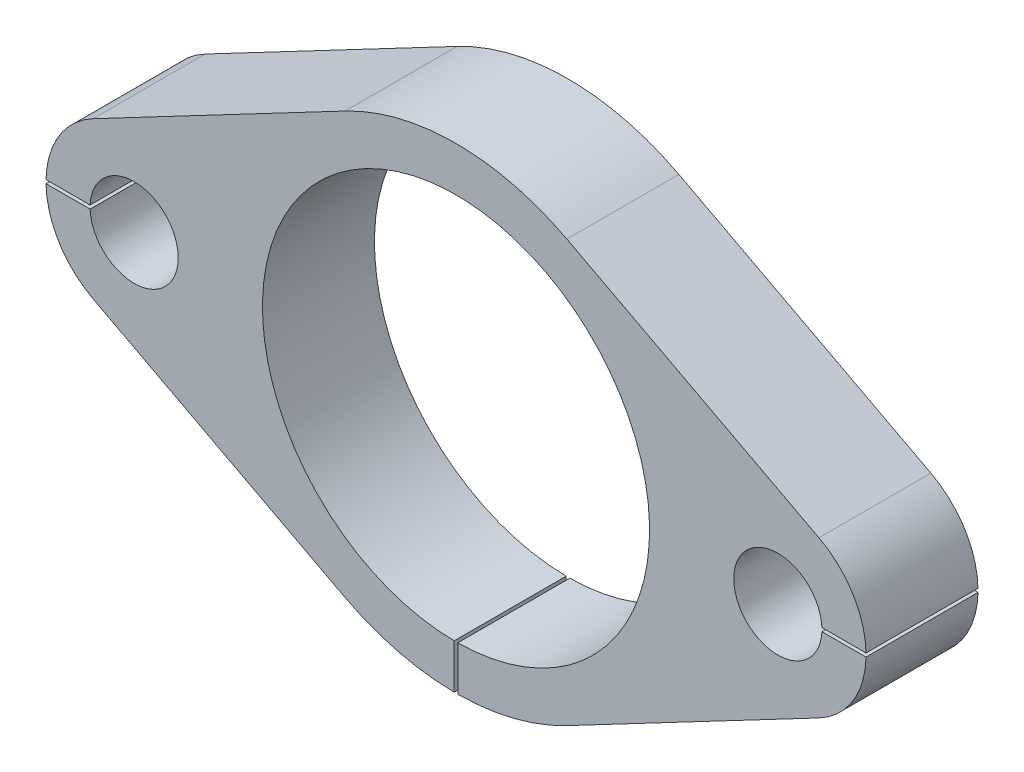
SolidWorks part; units mm, degrees
material "Chapa Grossa 1020 - 1/4\""
ref_plane "Plano frontal" through (0, 0, 0) normal (0, 0, 1) x (1, 0, 0)
ref_plane "Plano superior" through (0, 0, 0) normal (0, 1, 0) x (1, 0, 0)
ref_plane "Plano direito" through (0, 0, 0) normal (1, 0, 0) x (0, 0, -1)
sketch "Esboço1" plane through (0, 0, 0) normal (0, 0, 1) x (1, 0, 0)
  line L0 (-18.25, 0) -> (18.25, 0) construction
  line L1 (-20.5788, 4.4246) -> (-6.2877, 11.9463)
  line L2 (20.5788, 4.4246) -> (6.2877, 11.9463)
  line L3 (-20.5788, -4.4246) -> (-6.2877, -11.9463)
  line L4 (20.5788, -4.4246) -> (6.2877, -11.9463)
  arc A0 (6.2877, 11.9463) -> (-6.2877, 11.9463) centre (0, 0) ccw
  arc A1 (-20.5788, 4.4246) -> (-20.5788, -4.4246) centre (-18.25, 0) ccw
  arc A2 (20.5788, -4.4246) -> (20.5788, 4.4246) centre (18.25, 0) ccw
  arc A3 (-6.2877, -11.9463) -> (6.2877, -11.9463) centre (0, 0) ccw
  point P5 (0, 0)
  dimension "D2" = 13.5
  dimension "D3" = 5
  dimension "D1" = 36.5
extrude "Ressalto-extrusão1" add sketch "Esboço1" along normal blind 6.35
sketch "Esboço2" plane through (0, 0, 6.35) normal (0, 0, 1) x (1, 0, 0)
  circle A0 centre (0, 0) radius 10.975
  circle A1 centre (-18.25, 0) radius 2.5
  circle A2 centre (18.25, 0) radius 2.5
  dimension "D1" = 21.95
  dimension "D2" = 5
extrude "Corte-extrusão1" cut sketch "Esboço2" against normal through all
sketch "Esboço3" plane through (0, 0, 6.35) normal (0, 0, 1) x (1, 0, 0)
  line L0 (0, 0) -> (0, -13.5) construction
  line L1 (0.1, -10.9745) -> (0.1, -13.4996)
  line L2 (-0.1, -10.9745) -> (-0.1, -13.4996)
  arc A0 (-6.2877, -11.9463) -> (6.2877, -11.9463) centre (0, 0) ccw construction
  circle A1 centre (0, 0) radius 10.975 construction
  arc A2 (-0.1, -10.9745) -> (0.1, -10.9745) centre (0, 0) ccw
  arc A3 (-0.1, -13.4996) -> (0.1, -13.4996) centre (0, 0) ccw
  dimension "D1" = 0.2
extrude "Corte-extrusão2" cut sketch "Esboço3" against normal through all
sketch "Esboço4" plane through (0, 0, 6.35) normal (0, 0, 1) x (1, 0, 0)
  line L0 (-23.25, 0) -> (-18.25, 0) construction
  line L2 (-23.25, 0.1) -> (-18.25, 0.1)
  line L3 (-23.25, 0.1) -> (-23.25, -0.1)
  line L4 (-23.25, -0.1) -> (-18.25, -0.1)
  line L5 (-18.25, 0.1) -> (-18.25, -0.1)
  arc A0 (-20.5788, 4.4246) -> (-20.5788, -4.4246) centre (-18.25, 0) ccw construction
  point P10 (-18.25, 0)
  dimension "D1" = 0.2
extrude "Corte-extrusão3" cut sketch "Esboço4" against normal through all
mirror "Espelhar1" about plane through (0, 0, 0) normal (1, 0, 0) of "Corte-extrusão3"
